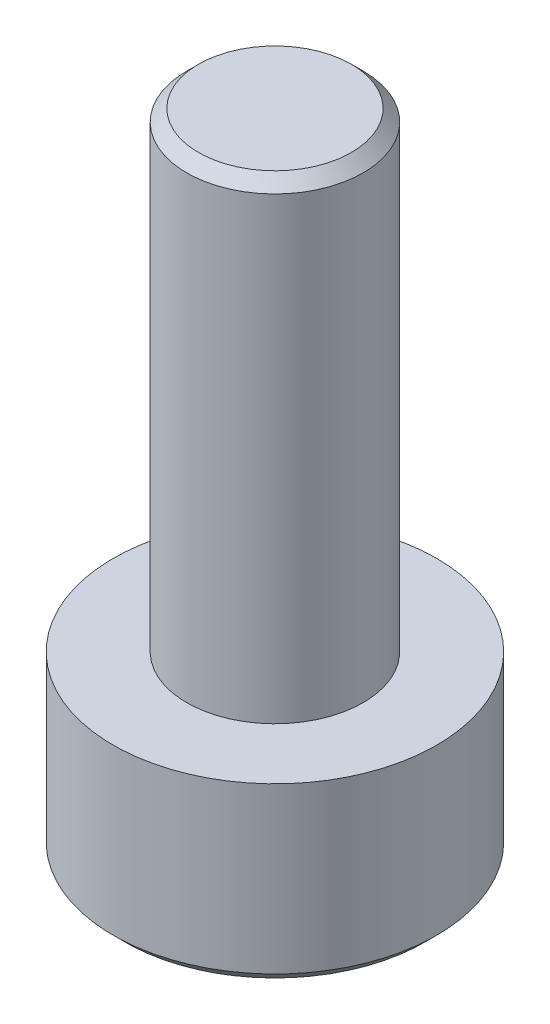
SolidWorks part; units mm, degrees
ref_plane "Front Plane" through (0, 0, 0) normal (0, 0, 1) x (1, 0, 0)
ref_plane "Top Plane" through (0, 0, 0) normal (0, 1, 0) x (1, 0, 0)
ref_plane "Right Plane" through (0, 0, 0) normal (1, 0, 0) x (0, 0, -1)
sketch "Reconstructed nominal axial profile" plane through (0, 0, 0) normal (0, 0, 1) x (1, 0, 0)
  line L0 (0, -500) -> (0, 50) construction
  line L1 (0, -3) -> (2.55, -3)
  line L2 (2.55, -3) -> (2.75, -2.8)
  line L3 (2.75, -2.8) -> (2.75, 0)
  line L4 (2.75, 0) -> (1.5, 0)
  line L5 (1.5, 0) -> (1.5, 7.8)
  line L6 (1.5, 7.8) -> (1.3, 8)
  line L7 (1.3, 8) -> (0, 8)
  line L8 (0, 8) -> (0, -3)
revolve "Native revolved geometry" add sketch "Reconstructed nominal axial profile" angle 360 about L0
sketch "Sketch2" plane through (0, 0, 0) normal (0, 1, 0) x (1, 0, 0)
  line L0 (1.4434, 0) -> (0.7217, -1.25)
  line L1 (0.7217, -1.25) -> (-0.7217, -1.25)
  line L2 (-0.7217, -1.25) -> (-1.4434, 0)
  line L3 (-1.4434, 0) -> (-0.7217, 1.25)
  line L4 (-0.7217, 1.25) -> (0.7217, 1.25)
  line L5 (0.7217, 1.25) -> (1.4434, 0)
extrude "Simplified nominal hex socket" cut sketch "Sketch2" along normal blind 1.5 from offset 3
